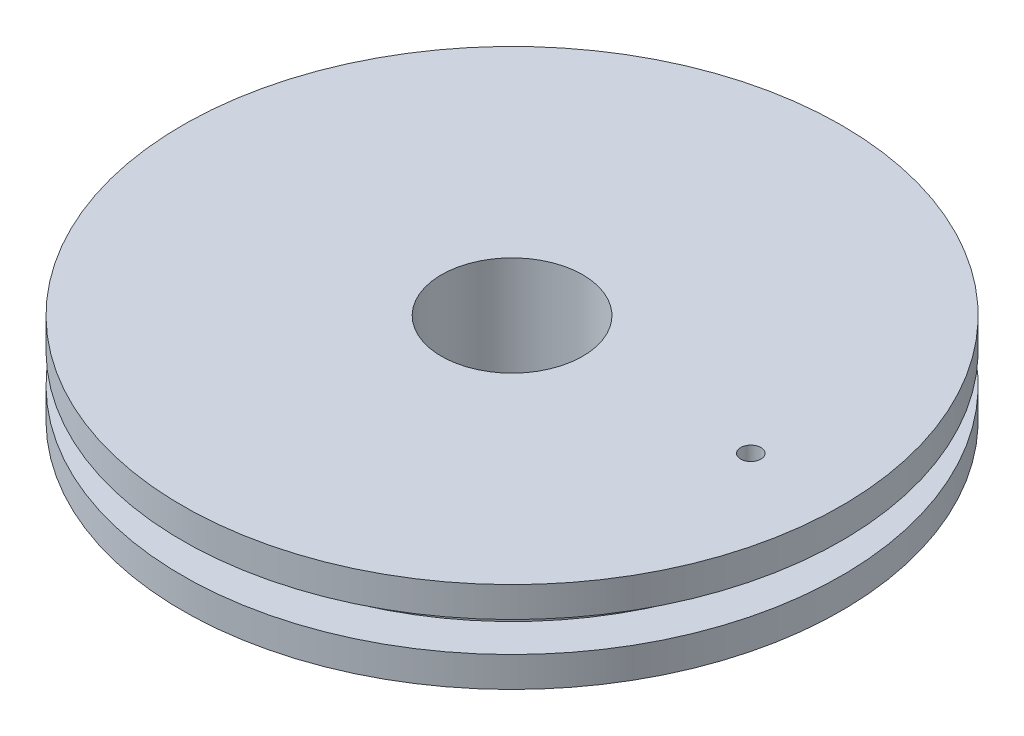
SolidWorks part; units mm, degrees
ref_plane "Front Plane" through (0, 0, 0) normal (0, 0, 1) x (1, 0, 0)
ref_plane "Top Plane" through (0, 0, 0) normal (0, 1, 0) x (1, 0, 0)
ref_plane "Right Plane" through (0, 0, 0) normal (1, 0, 0) x (0, 0, -1)
sketch "Sketch1" plane through (0, 0, 0) normal (0, 0, 1) x (1, 0, 0)
  line L0 (0, 0) -> (3.6404, 0) construction
  line L1 (32.65, -4.5) -> (10, -4.5)
  line L2 (7, 4.5) -> (32.65, 4.5)
  line L3 (32.65, 4.5) -> (32.65, 1.5)
  line L4 (32.65, 1.5) -> (28.65, 1.5)
  line L5 (28.65, 1.5) -> (28.65, -1.5)
  line L6 (35.915, 0) -> (-35.915, 0) construction
  line L7 (32.65, -4.5) -> (32.65, -1.5)
  line L8 (32.65, -1.5) -> (28.65, -1.5)
  line L9 (7, -17.5) -> (10, -17.5)
  line L10 (7, 4.5) -> (7, -17.5)
  line L11 (0, 0) -> (0, 14.7507) construction
  line L12 (10, -4.5) -> (10, -17.5)
  point P8 (32.65, -3)
  point P14 (28.65, 0)
  dimension "D1" = 14
  dimension "D2" = 3
  dimension "D3" = 3
  dimension "D4" = 4
  dimension "D5" = 57.3
  dimension "D6" = 20
  dimension "D7" = 13
revolve "Revolve1" add sketch "Sketch1" angle 360 about L11
sketch "Sketch2" plane through (0, 4.5, 0) normal (0, 1, 0) x (1, 0, 0)
  line L0 (-10.45, 0) -> (10.45, 0) construction
  line L1 (28.65, 1.3747) -> (28.65, 0) construction
  circle A0 centre (23.65, 0) radius 1
  circle A2 centre (0, 0) radius 28.65 construction
  circle A3 centre (0, 0) radius 28.65 construction
  point P11 (32.65, 0)
  dimension "D1" = 2
  dimension "D2" = 10
extrude "Cut-Extrude1" cut sketch "Sketch2" against normal through all
